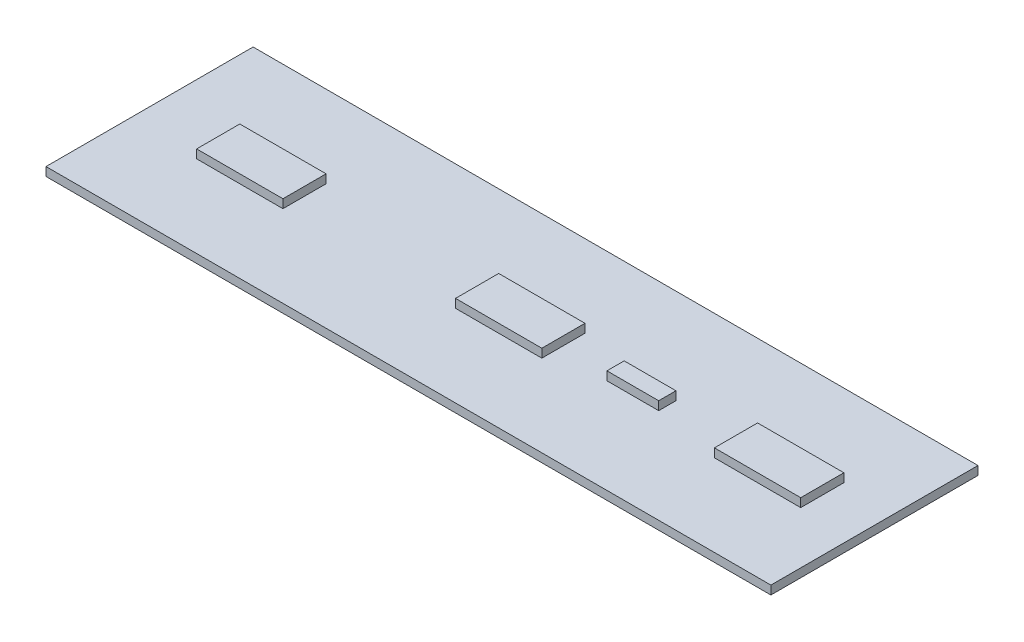
SolidWorks part; units mm, degrees
ref_plane "Спереди" through (0, 0, 0) normal (0, 0, 1) x (1, 0, 0)
ref_plane "Сверху" through (0, 0, 0) normal (0, 1, 0) x (1, 0, 0)
ref_plane "Справа" through (0, 0, 0) normal (1, 0, 0) x (0, 0, -1)
sketch "Эскиз1" plane through (0, 0, 0) normal (0, 1, 0) x (1, 0, 0)
  line L1 (-24.7816, 4.908) -> (17.2184, 4.908)
  line L2 (-24.7816, 4.908) -> (-24.7816, -7.092)
  line L3 (-24.7816, -7.092) -> (17.2184, -7.092)
  line L4 (17.2184, 4.908) -> (17.2184, -7.092)
  dimension "D1" = 42
  dimension "D2" = 12
extrude "Бобышка-Вытянуть1" add sketch "Эскиз1" along normal blind 0.5
sketch "Эскиз2" plane through (0, 0.5, 0) normal (0, 1, 0) x (1, 0, 0)
  line L0 (-24.7816, 4.908) -> (17.2184, -7.092) construction
  line L1 (18.9327, -1.092) -> (-31.0744, -1.092) construction
  line L2 (-24.7816, -7.092) -> (17.2184, 4.908) construction
  line L3 (-5.803, 0.158) -> (-5.803, -2.342)
  line L4 (9.197, 0.158) -> (14.197, 0.158)
  line L5 (9.197, 0.158) -> (9.197, -2.342)
  line L6 (9.197, -2.342) -> (14.197, -2.342)
  line L7 (14.197, 0.158) -> (14.197, -2.342)
  line L8 (9.197, 0.158) -> (14.197, -2.342) construction
  line L9 (9.197, -2.342) -> (14.197, 0.158) construction
  line L10 (-5.803, 0.158) -> (-0.803, 0.158)
  line L11 (-0.803, 0.158) -> (-0.803, -2.342)
  line L12 (-5.803, -2.342) -> (-0.803, -2.342)
  line L13 (-20.803, 0.158) -> (-20.803, -2.342)
  line L14 (-20.803, 0.158) -> (-15.803, 0.158)
  line L15 (-15.803, 0.158) -> (-15.803, -2.342)
  line L16 (-20.803, -2.342) -> (-15.803, -2.342)
  line L17 (17.2184, -7.092) -> (17.2184, 4.908) construction
  line L18 (2.2184, -0.592) -> (5.2184, -0.592)
  line L19 (2.2184, -0.592) -> (2.2184, -1.592)
  line L20 (2.2184, -1.592) -> (5.2184, -1.592)
  line L21 (5.2184, -0.592) -> (5.2184, -1.592)
  line L22 (2.2184, -0.592) -> (5.2184, -1.592) construction
  line L23 (2.2184, -1.592) -> (5.2184, -0.592) construction
  point P10 (11.697, -1.092)
  point P16 (3.7184, -1.092)
  point P30 (5.2184, -1.092)
  dimension "D1" = 5
  dimension "D2" = 2.5
  dimension "D3" = 3
  dimension "D4" = 10
  dimension "D5" = 3
  dimension "D6" = 1
  dimension "D7" = 12
extrude "Бобышка-Вытянуть2" add sketch "Эскиз2" along normal blind 0.5
